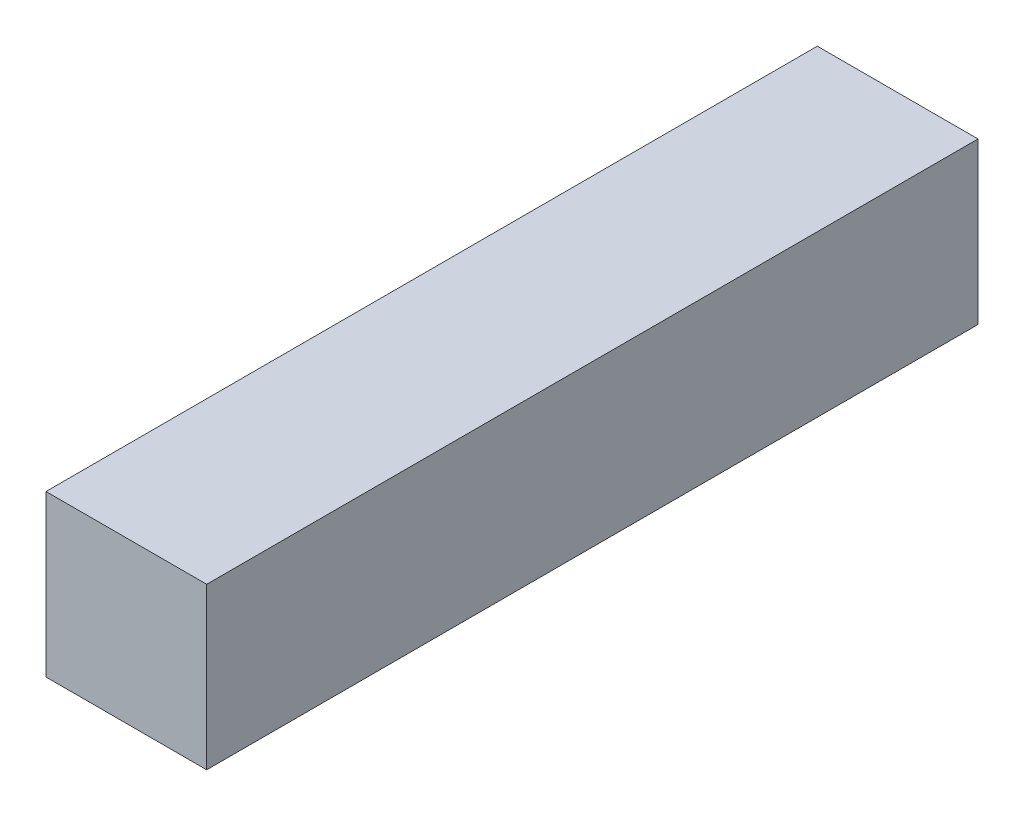
SolidWorks part; units mm, degrees
ref_plane "Front Plane" through (0, 0, 0) normal (0, 0, 1) x (1, 0, 0)
ref_plane "Top Plane" through (0, 0, 0) normal (0, 1, 0) x (1, 0, 0)
ref_plane "Right Plane" through (0, 0, 0) normal (1, 0, 0) x (0, 0, -1)
ref_plane "Plane1" through (7.5, 0, 0) normal (1, 0, 0) x (0, 0, -1)
sketch "Sketch1" plane through (7.5, 0, 0) normal (1, 0, 0) x (0, 0, -1)
  line L0 (0, -7.5) -> (0, 7.5)
  line L1 (0, 7.5) -> (-72, 7.5)
  line L2 (-72, 7.5) -> (-72, -7.5)
  line L3 (-72, -7.5) -> (0, -7.5)
extrude "Boss-Extrude1" add sketch "Sketch1" against normal blind 15
